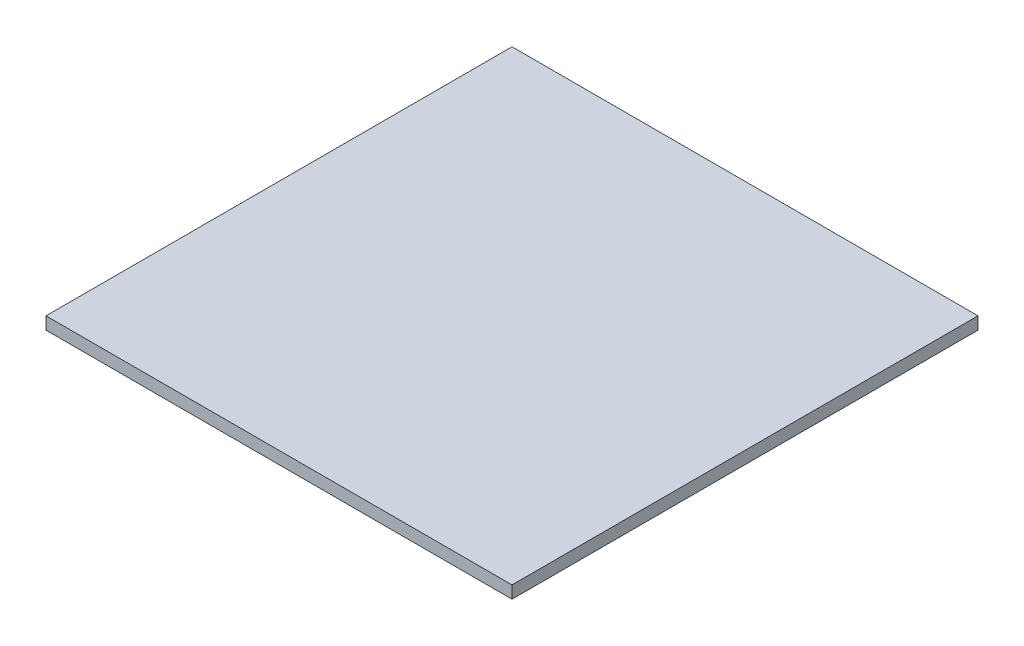
SolidWorks part; units mm, degrees
ref_plane "Front Plane" through (0, 0, 0) normal (0, 0, 1) x (1, 0, 0)
ref_plane "Top Plane" through (0, 0, 0) normal (0, 1, 0) x (1, 0, 0)
ref_plane "Right Plane" through (0, 0, 0) normal (1, 0, 0) x (0, 0, -1)
other "Configuration Table"
sketch "Sketch1" plane through (0, 0, 0) normal (0, 0, 1) x (1, 0, 0)
  line L1 (200, 862) -> (500, 862)
  line L2 (200, 862) -> (200, 870)
  line L3 (200, 870) -> (500, 870)
  line L4 (500, 862) -> (500, 870)
extrude "OVEN_damlalik_tavasi_1" add sketch "Sketch1" against normal blind 300 from offset 150 separate body
